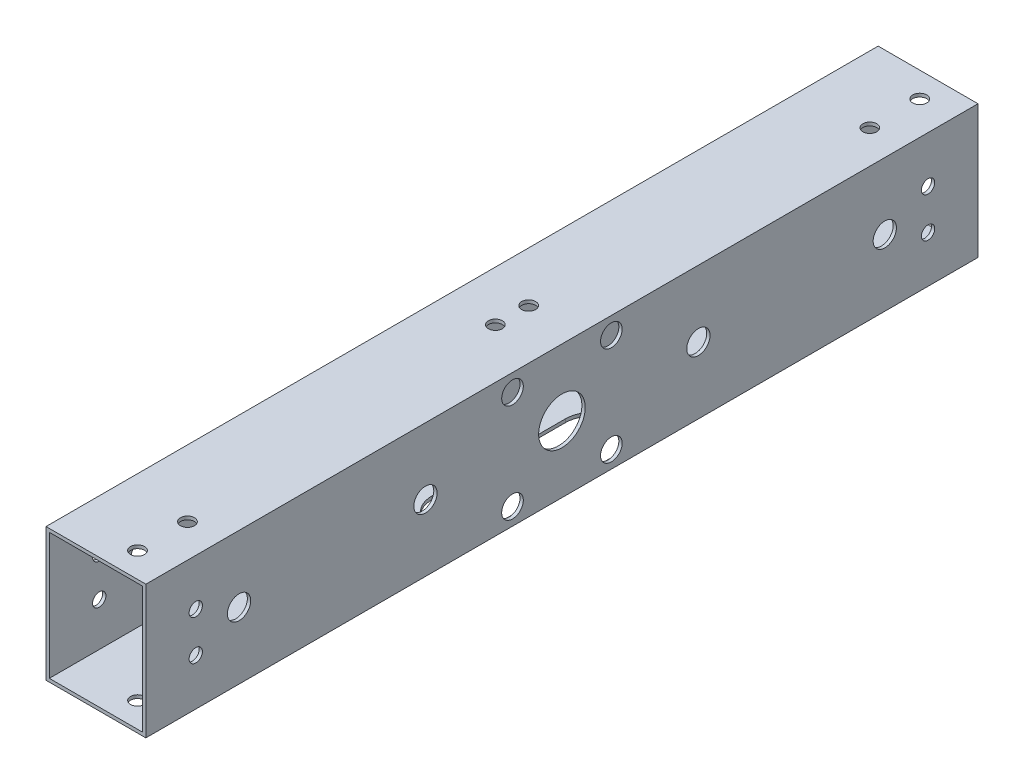
SolidWorks part; units mm, degrees
material "6061 合金"
ref_plane "前视基准面" through (0, 0, 0) normal (0, 0, 1) x (1, 0, 0)
ref_plane "上视基准面" through (0, 0, 0) normal (0, 1, 0) x (1, 0, 0)
ref_plane "右视基准面" through (0, 0, 0) normal (1, 0, 0) x (0, 0, -1)
other "Configuration Table"
sketch "草图1" plane through (0, 0, 0) normal (0, 0, 1) x (1, 0, 0)
  line L0 (15, -20) -> (15, 20)
  line L1 (15, 20) -> (-15, 20)
  line L2 (-15, 20) -> (-15, -20)
  line L3 (-15, -20) -> (15, -20)
  line L4 (14, 19) -> (-14, 19)
  line L5 (14, -19) -> (14, 19)
  line L6 (-14, -19) -> (14, -19)
  line L7 (-14, 19) -> (-14, -19)
extrude "凸台-拉伸1" add sketch "草图1" along normal blind 250
sketch "草图3" plane through (0, 20, 0) normal (0, 1, 0) x (1, 0, 0)
  line L0 (15, 0) -> (-15, 0) construction
  line L2 (-15, -125) -> (78.6025, -125) construction
  line L4 (-15, -250) -> (-15, 0) construction
  circle A0 centre (5, -7.5) radius 2.1
  circle A1 centre (5, -22.5) radius 2.1
  circle A4 centre (5, -227.5) radius 2.1
  circle A5 centre (5, -242.5) radius 2.1
  circle A6 centre (0, -120) radius 2.1
  circle A7 centre (0, -130) radius 2.1
  dimension "D1" = 4.2
  dimension "D2" = 7.5
  dimension "D4" = 20
  dimension "D5" = 4.2
  dimension "D6" = 10
  dimension "D3" = 2
extrude "切除-拉伸1" cut sketch "草图3" against normal blind 250
sketch "草图4" plane through (15, 0, 0) normal (1, 0, 0) x (0, 0, -1)
  line L0 (-250, 20) -> (0, 20) construction
  line L2 (-125, 20) -> (-125, -104.7599) construction
  line L3 (-84, 0) -> (-28, 0) construction
  line L5 (0, -20) -> (0, 20) construction
  circle A0 centre (-84, 0) radius 3.5
  circle A1 centre (-166, 0) radius 3.5
  circle A2 centre (-28, 0) radius 3.5
  circle A3 centre (-222, 0) radius 3.5
  circle A4 centre (-166, 0) radius 3.5
  dimension "D1" = 7
  dimension "D2" = 20
  dimension "D3" = 28
  dimension "D4" = 7
  dimension "D5" = 56
  dimension "D6" = 20
extrude "切除-拉伸2" cut sketch "草图4" against normal blind 250 contours A3 | A1 | A0 | A2
sketch "草图5" plane through (-15, 0, 0) normal (-1, 0, 0) x (0, 0, 1)
  line L0 (250, 20) -> (0, 20) construction
  line L1 (250, 20) -> (250, -20) construction
  circle A0 centre (125, 0) radius 7
  dimension "D1" = 20
  dimension "D2" = 14
  dimension "D3" = 125
extrude "切除-拉伸3" cut sketch "草图5" against normal blind 250
sketch "草图6" plane through (0, -20, 0) normal (0, -1, 0) x (1, 0, 0)
  line L0 (-15, 250) -> (-15, 0) construction
  line L2 (-4, 145) -> (-4, 105)
  line L4 (13, 145) -> (13, 105)
  line L5 (-15, 125) -> (57.9688, 125) construction
  line L6 (15, 250) -> (15, 0) construction
  arc A0 (13, 145) -> (-4, 145) centre (4.5, 145) ccw
  arc A1 (-4, 105) -> (13, 105) centre (4.5, 105) ccw
  dimension "D4" = 20
  dimension "D5" = 8.5
  dimension "D7" = 10.5
  dimension "D8" = 8.5
  dimension "D2" = 11
  dimension "D1" = 17
  dimension "D3" = 40
  dimension "D6" = 2
extrude "切除-拉伸4" cut sketch "草图6" against normal blind 20
sketch "草图8" plane through (-15, 0, 0) normal (-1, 0, 0) x (0, 0, 1)
  line L0 (125, 20) -> (125, -55.4072) construction
  line L1 (250, 20) -> (0, 20) construction
  line L2 (110.1508, 14.8492) -> (139.8492, 14.8492)
  line L3 (139.8492, 14.8492) -> (139.8492, -14.8492)
  circle A0 centre (110.1508, -14.8492) radius 3.25
  circle A1 centre (139.8492, -14.8492) radius 3.25
  circle A2 centre (110.1508, 14.8492) radius 3.25
  circle A3 centre (139.8492, 14.8492) radius 3.25
  circle A5 centre (125, 0) radius 21 construction
  dimension "D1" = 42
  dimension "D5" = 6.5
  dimension "D3" = 2
extrude "切除-拉伸7" cut sketch "草图8" against normal blind 22 from offset 20 offset against normal yes
sketch "草图9" plane through (15, 0, 0) normal (1, 0, 0) x (0, 0, -1)
  line L1 (0, -20) -> (0, 20) construction
  line L2 (-15, 6) -> (-15, -6) construction
  line L3 (-125, 20) -> (-125, -94.4562) construction
  line L4 (-250, 20) -> (0, 20) construction
  line L5 (-235, 6) -> (-235, -6) construction
  line L6 (-250, -20) -> (0, -20) construction
  circle A0 centre (-15, 6) radius 2
  circle A1 centre (-15, -6) radius 2
  circle A2 centre (-235, -6) radius 2
  circle A3 centre (-235, 6) radius 2
  dimension "D1" = 4
  dimension "D2" = 4
  dimension "D3" = 14
  dimension "D4" = 12
  dimension "D5" = 15
extrude "切除-拉伸8" cut sketch "草图9" against normal blind 36
ref_plane "基准面1" through (15, 20, 0) normal (0, 0, -1) x (-1, 0, 0)
